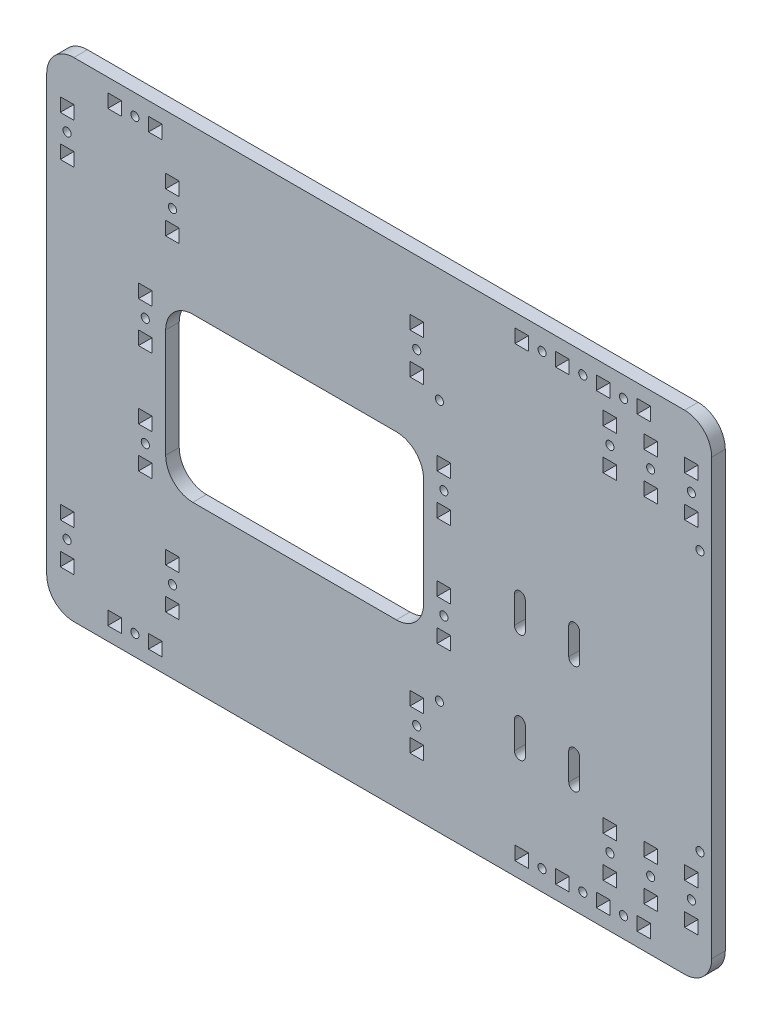
SolidWorks part; units mm, degrees
ref_plane "Front Plane" through (0, 0, 0) normal (0, 0, 1) x (1, 0, 0)
ref_plane "Top Plane" through (0, 0, 0) normal (0, 1, 0) x (1, 0, 0)
ref_plane "Right Plane" through (0, 0, 0) normal (1, 0, 0) x (0, 0, -1)
sketch "Sketch1" plane through (0, 0, 0) normal (0, 0, 1) x (1, 0, 0)
  line L0 (0, 0) -> (264.3375, 0) construction
  line L1 (-91.3244, 90) -> (153.676, 90)
  line L3 (-91.3244, -90) -> (153.676, -90)
  line L5 (23.6756, 97.7888) -> (23.6756, -107.1048) construction
  line L6 (-92.4996, 82.5) -> (92.5, 82.5) construction
  line L7 (92.5, -82.5) -> (-92.4996, -82.5) construction
  line L8 (-91.3244, 90) -> (-91.3244, -90)
  line L17 (53.355, -48) -> (53.355, 48) construction
  line L29 (53.355, -48) -> (149.355, -48) construction
  line L49 (53.355, 48) -> (149.355, 48) construction
  line L50 (149.355, -48) -> (149.355, 48) construction
  line L51 (-83.8244, 77.0051) -> (-83.8244, -67.4641) construction
  line L97 (-47.5, 30) -> (47.5, 30)
  line L98 (-47.5, 30) -> (-47.5, -30)
  line L99 (-47.5, -30) -> (47.5, -30)
  line L100 (47.5, 30) -> (47.5, -30)
  line L105 (103, -45) -> (49.07, -45) construction
  line L106 (103, -5) -> (73.57, -5) construction
  line L107 (103, -5) -> (103, -45) construction
  line L108 (103, -10) -> (103, 0) construction
  line L109 (101, -10) -> (101, 0)
  line L110 (105, -10) -> (105, 0)
  line L111 (83, -10) -> (83, 0) construction
  line L112 (81, -10) -> (81, 0)
  line L113 (85, -10) -> (85, 0)
  line L114 (83, -50) -> (83, -40) construction
  line L115 (81, -50) -> (81, -40)
  line L116 (85, -50) -> (85, -40)
  line L117 (103, -50) -> (103, -40) construction
  line L118 (101, -50) -> (101, -40)
  line L119 (105, -50) -> (105, -40)
  line L122 (153.676, 90) -> (153.676, -90)
  line L124 (-83.8244, 65) -> (153.676, 65) construction
  line L125 (-83.8244, -65) -> (153.676, -65) construction
  line L126 (55, -20) -> (55, 20) construction
  line L127 (0, 0) -> (0, 60.4175) construction
  arc A4 (101, -10) -> (105, -10) centre (103, -10) ccw
  arc A5 (105, 0) -> (101, 0) centre (103, 0) ccw
  arc A6 (81, -10) -> (85, -10) centre (83, -10) ccw
  arc A7 (85, 0) -> (81, 0) centre (83, 0) ccw
  arc A8 (81, -50) -> (85, -50) centre (83, -50) ccw
  arc A9 (85, -40) -> (81, -40) centre (83, -40) ccw
  arc A10 (101, -50) -> (105, -50) centre (103, -50) ccw
  arc A11 (105, -40) -> (101, -40) centre (103, -40) ccw
  circle A12 centre (53.355, 48) radius 1.5
  circle A13 centre (149.355, 48) radius 1.5
  circle A14 centre (149.355, -48) radius 1.5
  circle A15 centre (53.355, -48) radius 1.5
  point P113 (103, -5)
  point P122 (83, -5)
  point P129 (83, -45)
  point P136 (103, -45)
  line B0 (-63.8248, 82.5) -> (-53.8248, 82.5) construction
  line B1 (-63.8248, 85) -> (-68.8248, 85)
  line B2 (-63.8248, 85) -> (-63.8248, 80)
  line B3 (-63.8248, 80) -> (-68.8248, 80)
  line B4 (-68.8248, 85) -> (-68.8248, 80)
  line B5 (-53.8248, 85) -> (-48.8248, 85)
  line B6 (-53.8248, 85) -> (-53.8248, 80)
  line B7 (-53.8248, 80) -> (-48.8248, 80)
  line B8 (-48.8248, 85) -> (-48.8248, 80)
  line B9 (-58.8248, 82.5) -> (-58.8248, 89.4724) construction
  circle B10 centre (-58.8248, 82.5) radius 1.5
  line B11 (111.176, 82.5) -> (101.176, 82.5) construction
  line B12 (111.176, 85) -> (116.176, 85)
  line B13 (111.176, 85) -> (111.176, 80)
  line B14 (111.176, 80) -> (116.176, 80)
  line B15 (116.176, 85) -> (116.176, 80)
  line B16 (101.176, 85) -> (96.176, 85)
  line B17 (101.176, 85) -> (101.176, 80)
  line B18 (101.176, 80) -> (96.176, 80)
  line B19 (96.176, 85) -> (96.176, 80)
  line B20 (106.176, 82.5) -> (106.176, 89.4724) construction
  circle B21 centre (106.176, 82.5) radius 1.5
  line B22 (111.176, -82.5) -> (101.176, -82.5) construction
  line B23 (111.176, -85) -> (116.176, -85)
  line B24 (111.176, -85) -> (111.176, -80)
  line B25 (111.176, -80) -> (116.176, -80)
  line B26 (116.176, -85) -> (116.176, -80)
  line B27 (101.176, -85) -> (96.176, -85)
  line B28 (101.176, -85) -> (101.176, -80)
  line B29 (101.176, -80) -> (96.176, -80)
  line B30 (96.176, -85) -> (96.176, -80)
  line B31 (106.176, -82.5) -> (106.176, -89.4724) construction
  circle B32 centre (106.176, -82.5) radius 1.5
  line B33 (-63.8248, -82.5) -> (-53.8248, -82.5) construction
  line B34 (-63.8248, -85) -> (-68.8248, -85)
  line B35 (-63.8248, -85) -> (-63.8248, -80)
  line B36 (-63.8248, -80) -> (-68.8248, -80)
  line B37 (-68.8248, -85) -> (-68.8248, -80)
  line B38 (-53.8248, -85) -> (-48.8248, -85)
  line B39 (-53.8248, -85) -> (-53.8248, -80)
  line B40 (-53.8248, -80) -> (-48.8248, -80)
  line B41 (-48.8248, -85) -> (-48.8248, -80)
  line B42 (-58.8248, -82.5) -> (-58.8248, -89.4724) construction
  circle B43 centre (-58.8248, -82.5) radius 1.5
  line B44 (55, 25) -> (55, 15) construction
  line B45 (57.5, 25) -> (57.5, 30)
  line B46 (57.5, 25) -> (52.5, 25)
  line B47 (52.5, 25) -> (52.5, 30)
  line B48 (57.5, 30) -> (52.5, 30)
  line B49 (57.5, 15) -> (57.5, 10)
  line B50 (57.5, 15) -> (52.5, 15)
  line B51 (52.5, 15) -> (52.5, 10)
  line B52 (57.5, 10) -> (52.5, 10)
  line B53 (55, 20) -> (61.9724, 20) construction
  circle B54 centre (55, 20) radius 1.5
  line B55 (-55, 25) -> (-55, 15) construction
  line B56 (-57.5, 25) -> (-57.5, 30)
  line B57 (-57.5, 25) -> (-52.5, 25)
  line B58 (-52.5, 25) -> (-52.5, 30)
  line B59 (-57.5, 30) -> (-52.5, 30)
  line B60 (-57.5, 15) -> (-57.5, 10)
  line B61 (-57.5, 15) -> (-52.5, 15)
  line B62 (-52.5, 15) -> (-52.5, 10)
  line B63 (-57.5, 10) -> (-52.5, 10)
  line B64 (-55, 20) -> (-61.9724, 20) construction
  circle B65 centre (-55, 20) radius 1.5
  line B66 (55, -25) -> (55, -15) construction
  line B67 (57.5, -25) -> (57.5, -30)
  line B68 (57.5, -25) -> (52.5, -25)
  line B69 (52.5, -25) -> (52.5, -30)
  line B70 (57.5, -30) -> (52.5, -30)
  line B71 (57.5, -15) -> (57.5, -10)
  line B72 (57.5, -15) -> (52.5, -15)
  line B73 (52.5, -15) -> (52.5, -10)
  line B74 (57.5, -10) -> (52.5, -10)
  line B75 (55, -20) -> (61.9724, -20) construction
  circle B76 centre (55, -20) radius 1.5
  line B77 (-55, -25) -> (-55, -15) construction
  line B78 (-57.5, -25) -> (-57.5, -30)
  line B79 (-57.5, -25) -> (-52.5, -25)
  line B80 (-52.5, -25) -> (-52.5, -30)
  line B81 (-57.5, -30) -> (-52.5, -30)
  line B82 (-57.5, -15) -> (-57.5, -10)
  line B83 (-57.5, -15) -> (-52.5, -15)
  line B84 (-52.5, -15) -> (-52.5, -10)
  line B85 (-57.5, -10) -> (-52.5, -10)
  line B86 (-55, -20) -> (-61.9724, -20) construction
  circle B87 centre (-55, -20) radius 1.5
  line B88 (45, 65) -> (45, 55) construction
  line B89 (47.5, 65) -> (47.5, 70)
  line B90 (47.5, 65) -> (42.5, 65)
  line B91 (42.5, 65) -> (42.5, 70)
  line B92 (47.5, 70) -> (42.5, 70)
  line B93 (47.5, 55) -> (47.5, 50)
  line B94 (47.5, 55) -> (42.5, 55)
  line B95 (42.5, 55) -> (42.5, 50)
  line B96 (47.5, 50) -> (42.5, 50)
  line B97 (45, 60) -> (51.9724, 60) construction
  circle B98 centre (45, 60) radius 1.5
  line B99 (-45, 65) -> (-45, 55) construction
  line B100 (-47.5, 65) -> (-47.5, 70)
  line B101 (-47.5, 65) -> (-42.5, 65)
  line B102 (-42.5, 65) -> (-42.5, 70)
  line B103 (-47.5, 70) -> (-42.5, 70)
  line B104 (-47.5, 55) -> (-47.5, 50)
  line B105 (-47.5, 55) -> (-42.5, 55)
  line B106 (-42.5, 55) -> (-42.5, 50)
  line B107 (-47.5, 50) -> (-42.5, 50)
  line B108 (-45, 60) -> (-51.9724, 60) construction
  circle B109 centre (-45, 60) radius 1.5
  line B110 (45, -65) -> (45, -55) construction
  line B111 (47.5, -65) -> (47.5, -70)
  line B112 (47.5, -65) -> (42.5, -65)
  line B113 (42.5, -65) -> (42.5, -70)
  line B114 (47.5, -70) -> (42.5, -70)
  line B115 (47.5, -55) -> (47.5, -50)
  line B116 (47.5, -55) -> (42.5, -55)
  line B117 (42.5, -55) -> (42.5, -50)
  line B118 (47.5, -50) -> (42.5, -50)
  line B119 (45, -60) -> (51.9724, -60) construction
  circle B120 centre (45, -60) radius 1.5
  line B121 (-45, -65) -> (-45, -55) construction
  line B122 (-47.5, -65) -> (-47.5, -70)
  line B123 (-47.5, -65) -> (-42.5, -65)
  line B124 (-42.5, -65) -> (-42.5, -70)
  line B125 (-47.5, -70) -> (-42.5, -70)
  line B126 (-47.5, -55) -> (-47.5, -50)
  line B127 (-47.5, -55) -> (-42.5, -55)
  line B128 (-42.5, -55) -> (-42.5, -50)
  line B129 (-47.5, -50) -> (-42.5, -50)
  line B130 (-45, -60) -> (-51.9724, -60) construction
  circle B131 centre (-45, -60) radius 1.5
  line B132 (96.176, 82.5) -> (86.176, 82.5) construction
  line B133 (96.176, 85) -> (101.176, 85)
  line B134 (96.176, 85) -> (96.176, 80)
  line B135 (96.176, 80) -> (101.176, 80)
  line B136 (101.176, 85) -> (101.176, 80)
  line B137 (86.176, 85) -> (81.176, 85)
  line B138 (86.176, 85) -> (86.176, 80)
  line B139 (86.176, 80) -> (81.176, 80)
  line B140 (81.176, 85) -> (81.176, 80)
  line B141 (91.176, 82.5) -> (91.176, 89.4724) construction
  circle B142 centre (91.176, 82.5) radius 1.5
  line B143 (126.176, 82.5) -> (116.176, 82.5) construction
  line B144 (126.176, 85) -> (131.176, 85)
  line B145 (126.176, 85) -> (126.176, 80)
  line B146 (126.176, 80) -> (131.176, 80)
  line B147 (131.176, 85) -> (131.176, 80)
  line B148 (116.176, 85) -> (111.176, 85)
  line B149 (116.176, 85) -> (116.176, 80)
  line B150 (116.176, 80) -> (111.176, 80)
  line B151 (111.176, 85) -> (111.176, 80)
  line B152 (121.176, 82.5) -> (121.176, 89.4724) construction
  circle B153 centre (121.176, 82.5) radius 1.5
  line B154 (96.176, -82.5) -> (86.176, -82.5) construction
  line B155 (96.176, -85) -> (101.176, -85)
  line B156 (96.176, -85) -> (96.176, -80)
  line B157 (96.176, -80) -> (101.176, -80)
  line B158 (101.176, -85) -> (101.176, -80)
  line B159 (86.176, -85) -> (81.176, -85)
  line B160 (86.176, -85) -> (86.176, -80)
  line B161 (86.176, -80) -> (81.176, -80)
  line B162 (81.176, -85) -> (81.176, -80)
  line B163 (91.176, -82.5) -> (91.176, -89.4724) construction
  circle B164 centre (91.176, -82.5) radius 1.5
  line B165 (126.176, -82.5) -> (116.176, -82.5) construction
  line B166 (126.176, -85) -> (131.176, -85)
  line B167 (126.176, -85) -> (126.176, -80)
  line B168 (126.176, -80) -> (131.176, -80)
  line B169 (131.176, -85) -> (131.176, -80)
  line B170 (116.176, -85) -> (111.176, -85)
  line B171 (116.176, -85) -> (116.176, -80)
  line B172 (116.176, -80) -> (111.176, -80)
  line B173 (111.176, -85) -> (111.176, -80)
  line B174 (121.176, -82.5) -> (121.176, -89.4724) construction
  circle B175 centre (121.176, -82.5) radius 1.5
  line B176 (-83.8244, 70) -> (-83.8244, 60) construction
  line B177 (-86.3244, 70) -> (-86.3244, 75)
  line B178 (-86.3244, 70) -> (-81.3244, 70)
  line B179 (-81.3244, 70) -> (-81.3244, 75)
  line B180 (-86.3244, 75) -> (-81.3244, 75)
  line B181 (-86.3244, 60) -> (-86.3244, 55)
  line B182 (-86.3244, 60) -> (-81.3244, 60)
  line B183 (-81.3244, 60) -> (-81.3244, 55)
  line B184 (-86.3244, 55) -> (-81.3244, 55)
  line B185 (-83.8244, 65) -> (-90.7968, 65) construction
  circle B186 centre (-83.8244, 65) radius 1.5
  line B187 (-83.8244, -60) -> (-83.8244, -70) construction
  line B188 (-86.3244, -60) -> (-86.3244, -55)
  line B189 (-86.3244, -60) -> (-81.3244, -60)
  line B190 (-81.3244, -60) -> (-81.3244, -55)
  line B191 (-86.3244, -55) -> (-81.3244, -55)
  line B192 (-86.3244, -70) -> (-86.3244, -75)
  line B193 (-86.3244, -70) -> (-81.3244, -70)
  line B194 (-81.3244, -70) -> (-81.3244, -75)
  line B195 (-86.3244, -75) -> (-81.3244, -75)
  line B196 (-83.8244, -65) -> (-90.7968, -65) construction
  circle B197 centre (-83.8244, -65) radius 1.5
  line B198 (146.176, 70) -> (146.176, 60) construction
  line B199 (143.676, 70) -> (143.676, 75)
  line B200 (143.676, 70) -> (148.676, 70)
  line B201 (148.676, 70) -> (148.676, 75)
  line B202 (143.676, 75) -> (148.676, 75)
  line B203 (143.676, 60) -> (143.676, 55)
  line B204 (143.676, 60) -> (148.676, 60)
  line B205 (148.676, 60) -> (148.676, 55)
  line B206 (143.676, 55) -> (148.676, 55)
  line B207 (146.176, 65) -> (139.2036, 65) construction
  circle B208 centre (146.176, 65) radius 1.5
  line B209 (146.176, -60) -> (146.176, -70) construction
  line B210 (143.676, -60) -> (143.676, -55)
  line B211 (143.676, -60) -> (148.676, -60)
  line B212 (148.676, -60) -> (148.676, -55)
  line B213 (143.676, -55) -> (148.676, -55)
  line B214 (143.676, -70) -> (143.676, -75)
  line B215 (143.676, -70) -> (148.676, -70)
  line B216 (148.676, -70) -> (148.676, -75)
  line B217 (143.676, -75) -> (148.676, -75)
  line B218 (146.176, -65) -> (139.2036, -65) construction
  circle B219 centre (146.176, -65) radius 1.5
  line B220 (131.176, -60) -> (131.176, -70) construction
  line B221 (128.676, -60) -> (128.676, -55)
  line B222 (128.676, -60) -> (133.676, -60)
  line B223 (133.676, -60) -> (133.676, -55)
  line B224 (128.676, -55) -> (133.676, -55)
  line B225 (128.676, -70) -> (128.676, -75)
  line B226 (128.676, -70) -> (133.676, -70)
  line B227 (133.676, -70) -> (133.676, -75)
  line B228 (128.676, -75) -> (133.676, -75)
  line B229 (131.176, -65) -> (124.2036, -65) construction
  circle B230 centre (131.176, -65) radius 1.5
  line B231 (116.176, -60) -> (116.176, -70) construction
  line B232 (113.676, -60) -> (113.676, -55)
  line B233 (113.676, -60) -> (118.676, -60)
  line B234 (118.676, -60) -> (118.676, -55)
  line B235 (113.676, -55) -> (118.676, -55)
  line B236 (113.676, -70) -> (113.676, -75)
  line B237 (113.676, -70) -> (118.676, -70)
  line B238 (118.676, -70) -> (118.676, -75)
  line B239 (113.676, -75) -> (118.676, -75)
  line B240 (116.176, -65) -> (109.2036, -65) construction
  circle B241 centre (116.176, -65) radius 1.5
  line B242 (131.176, 70) -> (131.176, 60) construction
  line B243 (128.676, 70) -> (128.676, 75)
  line B244 (128.676, 70) -> (133.676, 70)
  line B245 (133.676, 70) -> (133.676, 75)
  line B246 (128.676, 75) -> (133.676, 75)
  line B247 (128.676, 60) -> (128.676, 55)
  line B248 (128.676, 60) -> (133.676, 60)
  line B249 (133.676, 60) -> (133.676, 55)
  line B250 (128.676, 55) -> (133.676, 55)
  line B251 (131.176, 65) -> (124.2036, 65) construction
  circle B252 centre (131.176, 65) radius 1.5
  line B253 (116.176, 70) -> (116.176, 60) construction
  line B254 (113.676, 70) -> (113.676, 75)
  line B255 (113.676, 70) -> (118.676, 70)
  line B256 (118.676, 70) -> (118.676, 75)
  line B257 (113.676, 75) -> (118.676, 75)
  line B258 (113.676, 60) -> (113.676, 55)
  line B259 (113.676, 60) -> (118.676, 60)
  line B260 (118.676, 60) -> (118.676, 55)
  line B261 (113.676, 55) -> (118.676, 55)
  line B262 (116.176, 65) -> (109.2036, 65) construction
  circle B263 centre (116.176, 65) radius 1.5
  dimension "D22" = 45
  dimension "D23" = 10
  dimension "D8" = 3
  dimension "D24" = 2
  dimension "D28" = 40
  dimension "D1" = 165
  dimension "D2" = 7.5
  dimension "D4" = 32.4996
  dimension "D5" = 32.5
  dimension "D6" = 96
  dimension "D7" = 96
  dimension "D9" = 115
  dimension "D10" = 23.6756
  dimension "D11" = 28
  dimension "D12" = 47.5
  dimension "D13" = 7.5
  dimension "D14" = 25
  dimension "D15" = 40
  dimension "D17" = 60
  dimension "D18" = 7.5
  dimension "D19" = 15
  dimension "D20" = 15
  dimension "D21" = 7.5
  dimension "D25" = 2
  dimension "D27" = 20
  dimension "D33" = 60
  dimension "D26" = 2
sketch_block_instance "Trou M3 plots 5mm-1"
sketch_block "Trou M3 plots 5mm" parameters "D2"=3, "D1"=5, "D3"=5, "D4"=10
sketch_block_instance "Trou M3 plots 5mm-3"
sketch_block_instance "Trou M3 plots 5mm-4"
sketch_block_instance "Trou M3 plots 5mm-5"
sketch_block_instance "Trou M3 plots 5mm-7"
sketch_block_instance "Trou M3 plots 5mm-8"
sketch_block_instance "Trou M3 plots 5mm-9"
sketch_block_instance "Trou M3 plots 5mm-10"
sketch_block_instance "Trou M3 plots 5mm-11"
sketch_block_instance "Trou M3 plots 5mm-12"
sketch_block_instance "Trou M3 plots 5mm-13"
sketch_block_instance "Trou M3 plots 5mm-14"
sketch_block_instance "Trou M3 plots 5mm-15"
sketch_block_instance "Trou M3 plots 5mm-16"
sketch_block_instance "Trou M3 plots 5mm-18"
sketch_block_instance "Trou M3 plots 5mm-19"
sketch_block_instance "Trou M3 plots 5mm-20"
sketch_block_instance "Trou M3 plots 5mm-21"
sketch_block_instance "Trou M3 plots 5mm-22"
sketch_block_instance "Trou M3 plots 5mm-23"
sketch_block_instance "Trou M3 plots 5mm-24"
sketch_block_instance "Trou M3 plots 5mm-25"
sketch_block_instance "Trou M3 plots 5mm-26"
sketch_block_instance "Trou M3 plots 5mm-27"
extrude "Boss-Extrude1" add sketch "Sketch1" along normal blind 5 contours L122 L1 L8 L3 B175 B169 B166 B167 B168 B164 B144 B147 B146 B145 B142 B140 B137 B138 B139 B131 B125 B122 B123 B124 B111 B114 B113 B112 B109 B107 B104 B105 B106 B98 B92 B89 B90 B91
fillet "Fillet1" radius 10 8 edges at (-91.3244, 90, 2.5) (-91.3244, -90, 2.5) (153.676, 90, 2.5) (153.676, -90, 2.5) (-47.5, -30, 2.5) (-47.5, 30, 2.5) (47.5, 30, 2.5) (47.5, -30, 2.5)
